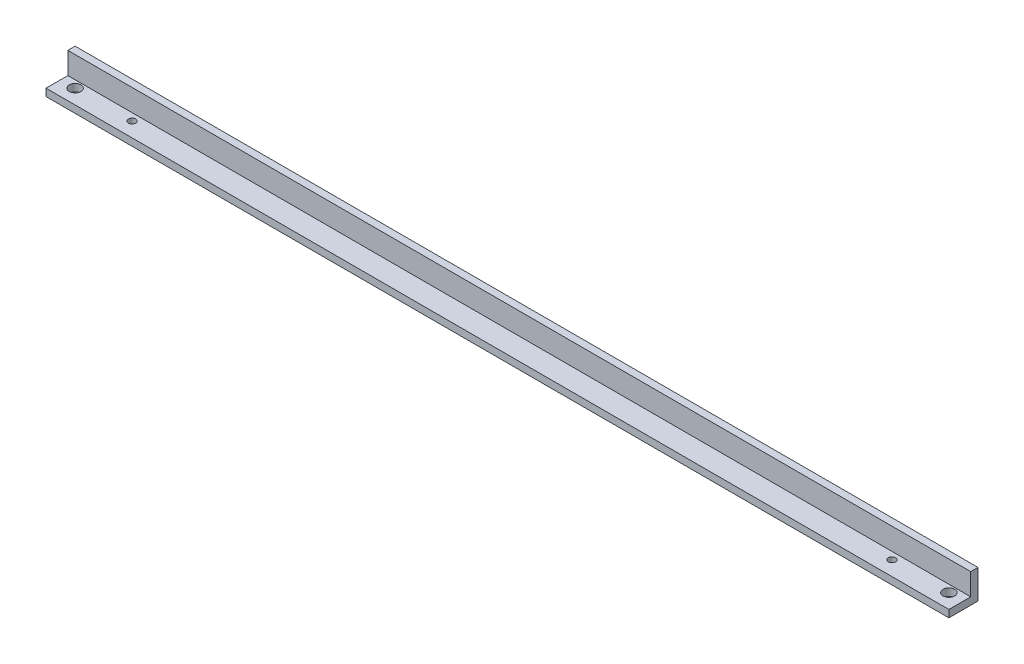
SolidWorks part; units mm, degrees
material "6061-T6 (SS)"
ref_plane "Front Plane" through (0, 0, 0) normal (0, 0, 1) x (1, 0, 0)
ref_plane "Top Plane" through (0, 0, 0) normal (0, 1, 0) x (1, 0, 0)
ref_plane "Right Plane" through (0, 0, 0) normal (1, 0, 0) x (0, 0, -1)
sketch "Sketch1" plane through (0, 0, 0) normal (1, 0, 0) x (0, 0, -1)
  line L0 (0, 0) -> (0, 19.05)
  line L1 (0, 19.05) -> (6.35, 19.05)
  line L2 (6.35, 19.05) -> (6.35, -6.35)
  line L3 (6.35, -6.35) -> (-19.05, -6.35)
  line L4 (-19.05, -6.35) -> (-19.05, 0)
  line L5 (-19.05, 0) -> (0, 0)
  dimension "D1" = 25.4
  dimension "D2" = 25.4
  dimension "D3" = 6.35
  dimension "D4" = 6.35
extrude "Boss-Extrude1" add sketch "Sketch1" along normal blind 787.4
sketch "Sketch2" plane through (0, -6.35, 0) normal (0, -1, 0) x (1, 0, 0)
  line L0 (0, 6.35) -> (787.4, 6.35) construction
  line L1 (0, 19.05) -> (0, -6.35) construction
  line L2 (393.7, 19.05) -> (393.7, -6.35) construction
  line L5 (787.4, 19.05) -> (787.4, -6.35) construction
  line L6 (787.4, 19.05) -> (0, 19.05) construction
  line L7 (787.4, -6.35) -> (0, -6.35) construction
  circle A0 centre (12.7, 6.35) radius 5.08
  circle A1 centre (62.357, 6.35) radius 3.175
  circle A8 centre (725.043, 6.35) radius 3.175
  circle A9 centre (774.7, 6.35) radius 5.08
  dimension "D1" = 10.16
  dimension "D2" = 6.35
  dimension "D3" = 12.7
  dimension "D4" = 49.657
extrude "Cut-Extrude1" cut sketch "Sketch2" against normal blind 914.4
